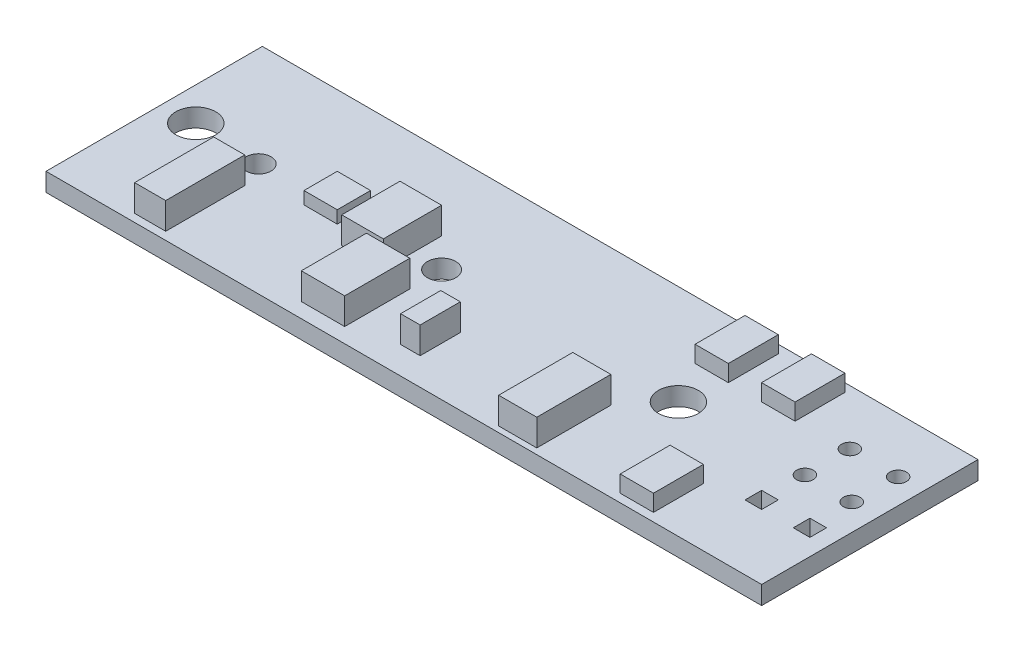
SolidWorks part; units mm, degrees
ref_plane "Front Plane" through (0, 0, 0) normal (0, 0, 1) x (1, 0, 0)
ref_plane "Top Plane" through (0, 0, 0) normal (0, 1, 0) x (1, 0, 0)
ref_plane "Right Plane" through (0, 0, 0) normal (1, 0, 0) x (0, 0, -1)
sketch "Sketch1" plane through (0, 0, 0) normal (0, 1, 0) x (1, 0, 0)
  line L0 (-993.1219, 7) -> (49006.8781, 7) construction
  line L1 (0, 0) -> (43, 0)
  line L2 (0, 0) -> (0, 13)
  line L3 (0, 13) -> (43, 13)
  line L4 (43, 0) -> (43, 13)
  line L6 (39.1, 4.9) -> (38.1, 4.9)
  line L7 (39.1, 4.9) -> (39.1, 3.9)
  line L8 (39.1, 3.9) -> (38.1, 3.9)
  line L9 (38.1, 4.9) -> (38.1, 3.9)
  line L10 (39.1, 4.9) -> (38.1, 3.9) construction
  line L11 (39.1, 3.9) -> (38.1, 4.9) construction
  line L12 (41, 4.9) -> (42, 4.9)
  line L13 (41, 4.9) -> (41, 3.9)
  line L14 (41, 3.9) -> (42, 3.9)
  line L15 (42, 4.9) -> (42, 3.9)
  line L16 (41, 4.9) -> (42, 3.9) construction
  line L17 (41, 3.9) -> (42, 4.9) construction
  circle A0 centre (2, 7) radius 1.2
  circle A1 centre (31, 7) radius 1.2
  circle A2 centre (38.6, 7) radius 0.5
  circle A3 centre (41.4127, 7) radius 0.5
  circle A4 centre (38.6, 9.7) radius 0.5
  circle A5 centre (41.5, 9.7) radius 0.5
  point P19 (38.6, 4.4)
  point P24 (41.5, 4.4)
  dimension "D5" = 2.4
  dimension "D6" = 2.4
  dimension "D9" = 1
  dimension "D10" = 1
  dimension "D11" = 1
  dimension "D12" = 1
  dimension "D1" = 43
  dimension "D2" = 13
  dimension "D3" = 7
  dimension "D4" = 6
  dimension "D7" = 2
  dimension "D8" = 29
  dimension "D13" = 1
  dimension "D14" = 1
  dimension "D15" = 1
  dimension "D16" = 1
  dimension "D17" = 1.5
  dimension "D18" = 1.5873
  dimension "D19" = 1.5
  dimension "D20" = 3.3
  dimension "D21" = 3.3
  dimension "D22" = 4.4
  dimension "D23" = 4.4
  dimension "D24" = 4.4
  dimension "D25" = 4.4
  dimension "D26" = 4.4
extrude "Boss-Extrude1" add sketch "Sketch1" along normal blind 1.1
sketch "Sketch3" plane through (0, 1.1, 0) normal (0, 1, 0) x (1, 0, 0)
  line L0 (-993.7919, 7) -> (49006.2081, 7) construction
  line L1 (43, 13) -> (0, 13) construction
  line L2 (0, 13) -> (0, 0) construction
  line L3 (9.5, 6) -> (11.5, 6)
  line L4 (9.5, 6) -> (9.5, 8)
  line L5 (9.5, 8) -> (11.5, 8)
  line L6 (11.5, 6) -> (11.5, 8)
  line L7 (9.5, 6) -> (11.5, 8) construction
  line L8 (9.5, 8) -> (11.5, 6) construction
  point P4 (10.5, 7)
  dimension "D1" = 6
  dimension "D2" = 10.5
  dimension "D3" = 2
  dimension "D4" = 2
sketch "Sketch4" plane through (0, 1.1, 0) normal (0, 1, 0) x (1, 0, 0)
  line L1 (10.2126, 7) -> (10.7874, 7)
  line L2 (10.2126, 7) -> (10.2126, 6.539)
  line L3 (10.2126, 6.539) -> (10.7874, 6.539)
  line L4 (10.7874, 7) -> (10.7874, 6.539)
  line L5 (10.2126, 7) -> (10.7874, 6.539) construction
  line L6 (10.2126, 6.539) -> (10.7874, 7) construction
  line L7 (-988.5, 7) -> (49011.5, 7) construction
  line L9 (10.5, -992) -> (10.5, 49008) construction
  line L11 (43, 13) -> (0, 13) construction
  line L12 (0, 13) -> (0, 0) construction
  point P0 (10.5, 6.7695)
  dimension "D1" = 6
  dimension "D2" = 10.5
extrude "Cut-Extrude3" cut sketch "Sketch4" against normal through all
sketch "Sketch2" plane through (0, 1.1, 0) normal (0, 1, 0) x (1, 0, 0)
  line L0 (-977.8286, 6.7695) -> (998.2537, 6.7695) construction
  line L2 (0, 13) -> (0, 0) construction
  line L8 (10.2126, 7) -> (10.2126, 6.539) construction
  circle A0 centre (6, 6.7695) radius 0.75
  point P1 (10.2126, 6.7695)
  dimension "D3" = 1.5
  dimension "D2" = 6
extrude "Cut-Extrude1" cut sketch "Sketch2" against normal blind 1.1
sketch "Sketch5" plane through (0, 1.1, 0) normal (0, 1, 0) x (1, 0, 0)
  line L0 (-989.7874, 6.7695) -> (49010.2126, 6.7695) construction
  line L1 (0, 13) -> (0, 0) construction
  line L3 (10.2126, 7) -> (10.2126, 6.539) construction
  circle A0 centre (14, 6.7695) radius 0.85
  circle A1 centre (17, 6.7695) radius 0.85
  point P12 (10.2126, 6.7695)
  dimension "D3" = 1.7
  dimension "D4" = 1.7
  dimension "D1" = 14
  dimension "D2" = 3
extrude "Cut-Extrude4" cut sketch "Sketch5" against normal through all
sketch "Sketch6" plane through (0, 1.1, 0) normal (0, 1, 0) x (1, 0, 0)
  line L1 (12.75, 8.0195) -> (15.25, 8.0195) construction
  line L2 (12.75, 8.0195) -> (12.75, 5.5195) construction
  line L3 (12.75, 5.5195) -> (15.25, 5.5195) construction
  line L4 (15.25, 8.0195) -> (15.25, 5.5195) construction
  line L5 (12.75, 8.0195) -> (15.25, 5.5195) construction
  line L6 (12.75, 5.5195) -> (15.25, 8.0195) construction
  line L7 (15.75, 8.5195) -> (18.25, 8.5195)
  line L8 (15.75, 8.5195) -> (15.75, 5.0195)
  line L9 (15.75, 5.0195) -> (18.25, 5.0195)
  line L10 (18.25, 8.5195) -> (18.25, 5.0195)
  line L11 (15.75, 8.5195) -> (18.25, 5.0195) construction
  line L12 (15.75, 5.0195) -> (18.25, 8.5195) construction
  circle A0 centre (14, 6.7695) radius 0.85 construction
  circle A1 centre (17, 6.7695) radius 0.85
  point P0 (14, 6.7695)
  point P6 (17, 6.7695)
  dimension "D1" = 2.5
  dimension "D2" = 2.5
  dimension "D3" = 3.5
  dimension "D4" = 2.5
extrude "Boss-Extrude2" [suppressed] add sketch "Sketch6" along normal blind 1.6
sketch "Sketch7" [suppressed] plane through (0, 2.7, 0) normal (0, 1, 0) x (1, 0, 0)
  circle A0 centre (14, 6.7695) radius 0.85 construction
  circle A1 centre (17, 6.7695) radius 0.85
extrude "Boss-Extrude3" [suppressed] add sketch "Sketch7" along normal blind 1.1 separate body
fillet "Fillet1" [suppressed] radius 0.85
fillet "Fillet2" [suppressed] radius 0.85
extrude "Boss-Extrude4" add sketch "Sketch3" along normal blind 0.75
sketch "Sketch8" plane through (0, 1.1, 0) normal (0, 1, 0) x (1, 0, 0)
  line L1 (4.8512, 5.2249) -> (6.7176, 5.2249)
  line L2 (4.8512, 5.2249) -> (4.8512, 0.4742)
  line L3 (4.8512, 0.4742) -> (6.7176, 0.4742)
  line L4 (6.7176, 5.2249) -> (6.7176, 0.4742)
  line L5 (4.8512, 5.2249) -> (6.7176, 0.4742) construction
  line L6 (4.8512, 0.4742) -> (6.7176, 5.2249) construction
  line L7 (14.447, 4.8061) -> (17.053, 4.8061)
  line L8 (14.447, 4.8061) -> (14.447, 0.893)
  line L9 (14.447, 0.893) -> (17.053, 0.893)
  line L10 (17.053, 4.8061) -> (17.053, 0.893)
  line L11 (14.447, 4.8061) -> (17.053, 0.893) construction
  line L12 (14.447, 0.893) -> (17.053, 4.8061) construction
  line L13 (19.6624, 4.0562) -> (20.8376, 4.0562)
  line L14 (19.6624, 4.0562) -> (19.6624, 1.6429)
  line L15 (19.6624, 1.6429) -> (20.8376, 1.6429)
  line L16 (20.8376, 4.0562) -> (20.8376, 1.6429)
  line L17 (19.6624, 4.0562) -> (20.8376, 1.6429) construction
  line L18 (19.6624, 1.6429) -> (20.8376, 4.0562) construction
  line L20 (26.8502, 4.8014) -> (29.14, 4.8014)
  line L21 (26.8502, 4.8014) -> (26.8502, 0.3484)
  line L22 (26.8502, 0.3484) -> (29.14, 0.3484)
  line L23 (29.14, 4.8014) -> (29.14, 0.3484)
  line L24 (26.8502, 4.8014) -> (29.14, 0.3484) construction
  line L25 (26.8502, 0.3484) -> (29.14, 4.8014) construction
  line L26 (12.75, 8.5195) -> (15.25, 8.5195)
  line L27 (12.75, 8.5195) -> (12.75, 5.0195)
  line L28 (12.75, 5.0195) -> (15.25, 5.0195)
  line L29 (15.25, 8.5195) -> (15.25, 5.0195)
  line L30 (12.75, 8.5195) -> (15.25, 5.0195) construction
  line L31 (12.75, 5.0195) -> (15.25, 8.5195) construction
  point P0 (5.7844, 2.8495)
  point P5 (15.75, 2.8495)
  point P10 (20.25, 2.8495)
  point P17 (27.9951, 2.5749)
  point P24 (14, 6.7695)
  dimension "D1" = 4.5
  dimension "D2" = 9.9656
  dimension "D3" = 7.75
  dimension "D4" = 3.5
  dimension "D5" = 2.5
extrude "Boss-Extrude5" add sketch "Sketch8" along normal blind 1.6
sketch "Sketch9" plane through (0, 1.1, 0) normal (0, 1, 0) x (1, 0, 0)
  line L0 (43, 0) -> (43, 13) construction
  line L1 (34, 3.5) -> (36, 3.5)
  line L2 (34, 3.5) -> (34, 0.5)
  line L3 (34, 0.5) -> (36, 0.5)
  line L4 (36, 3.5) -> (36, 0.5)
  line L5 (34, 3.5) -> (36, 0.5) construction
  line L6 (34, 0.5) -> (36, 3.5) construction
  line L7 (0, 0) -> (43, 0) construction
  line L8 (33.4935, 12.5) -> (35.5065, 12.5)
  line L9 (33.4935, 12.5) -> (33.4935, 9.5)
  line L10 (33.4935, 9.5) -> (35.5065, 9.5)
  line L11 (35.5065, 12.5) -> (35.5065, 9.5)
  line L12 (33.4935, 12.5) -> (35.5065, 9.5) construction
  line L13 (33.4935, 9.5) -> (35.5065, 12.5) construction
  line L14 (43, 13) -> (0, 13) construction
  line L15 (29.5, 12.5) -> (31.5, 12.5)
  line L16 (29.5, 12.5) -> (29.5, 9.5)
  line L17 (29.5, 9.5) -> (31.5, 9.5)
  line L18 (31.5, 12.5) -> (31.5, 9.5)
  line L19 (29.5, 12.5) -> (31.5, 9.5) construction
  line L20 (29.5, 9.5) -> (31.5, 12.5) construction
  point P0 (35, 2)
  point P7 (35, 0.5)
  point P10 (34.5, 11)
  point P18 (30.5, 11)
  dimension "D1" = 8
  dimension "D2" = 3
  dimension "D3" = 0.5
  dimension "D4" = 2
  dimension "D5" = 8.5
  dimension "D6" = 0.5
  dimension "D7" = 3
  dimension "D8" = 12.5
  dimension "D9" = 0.5
  dimension "D10" = 3
  dimension "D11" = 2
extrude "Boss-Extrude6" add sketch "Sketch9" along normal blind 1
sketch "Sketch11" plane through (0, 1.1, 0) normal (0, 1, 0) x (1, 0, 0)
  line L0 (15.25, 8.5195) -> (12.75, 8.5195) construction
  line L6 (12.75, 8.5195) -> (12.75, 5.0195) construction
  line L8 (-993.75, 6.7695) -> (49006.25, 6.7695) construction
  line L9 (14, -991.75) -> (14, 49008.25) construction
  circle A0 centre (14, 6.7695) radius 1
  point P6 (14, 8.5195)
  point P15 (12.75, 6.7695)
  dimension "D1" = 2
extrude "Boss-Extrude7" add sketch "Sketch11" along normal blind 1.4
fillet "Fillet3" [suppressed] radius 1
